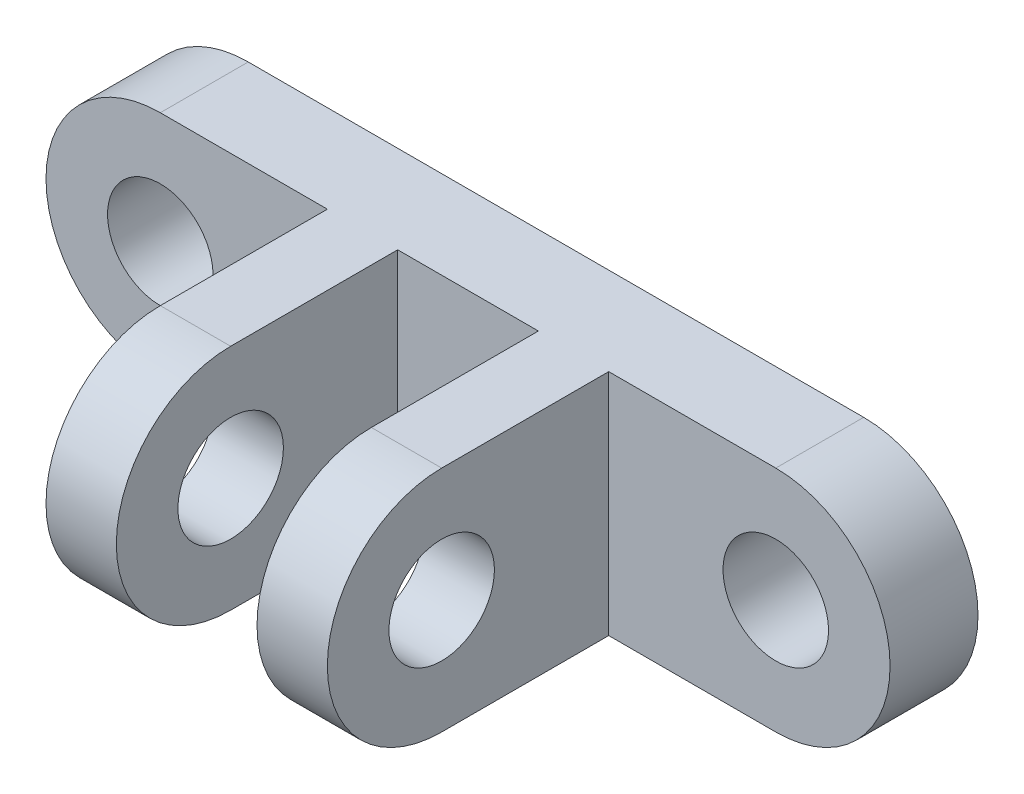
SolidWorks part; units mm, degrees
material "Cast Alloy Steel"
ref_plane "Front Plane" through (0, 0, 0) normal (0, 0, 1) x (1, 0, 0)
ref_plane "Top Plane" through (0, 0, 0) normal (0, 1, 0) x (1, 0, 0)
ref_plane "Right Plane" through (0, 0, 0) normal (1, 0, 0) x (0, 0, -1)
sketch "Sketch1" plane through (0, 0, 0) normal (0, 0, 1) x (1, 0, 0)
  line L0 (-35, 0) -> (35, 0) construction
  line L1 (-35, 13) -> (35, 13)
  line L2 (-35, -13) -> (35, -13)
  arc A0 (-35, 13) -> (-35, -13) centre (-35, 0) ccw
  arc A1 (35, -13) -> (35, 13) centre (35, 0) ccw
  circle A2 centre (-35, 0) radius 6
  circle A3 centre (35, 0) radius 6
  point P2 (0, 0)
  dimension "D1" = 13
  dimension "D3" = 12
  dimension "D2" = 70
extrude "Boss-Extrude1" add sketch "Sketch1" along normal blind 10
sketch "Sketch3" plane through (0, 0, 0) normal (1, 0, 0) x (0, 0, -1)
  line L0 (-1000, 0) -> (49000, 0) construction
  line L1 (0, -13) -> (0, 13) construction
  line L2 (-10, -13) -> (-29, -13)
  line L3 (-10, 13) -> (-29, 13)
  line L4 (-10, 13) -> (-10, -13) construction
  line L5 (-10, 13) -> (-10, -13)
  circle A0 centre (-29, 0) radius 6
  arc A1 (-29, 13) -> (-29, -13) centre (-29, 0) ccw
  dimension "D1" = 12
  dimension "D2" = 29
extrude "Boss-Extrude2" add sketch "Sketch3" along normal blind 8 from offset 8
mirror "Mirror1" about plane through (0, 0, 0) normal (1, 0, 0) of "Boss-Extrude2"
